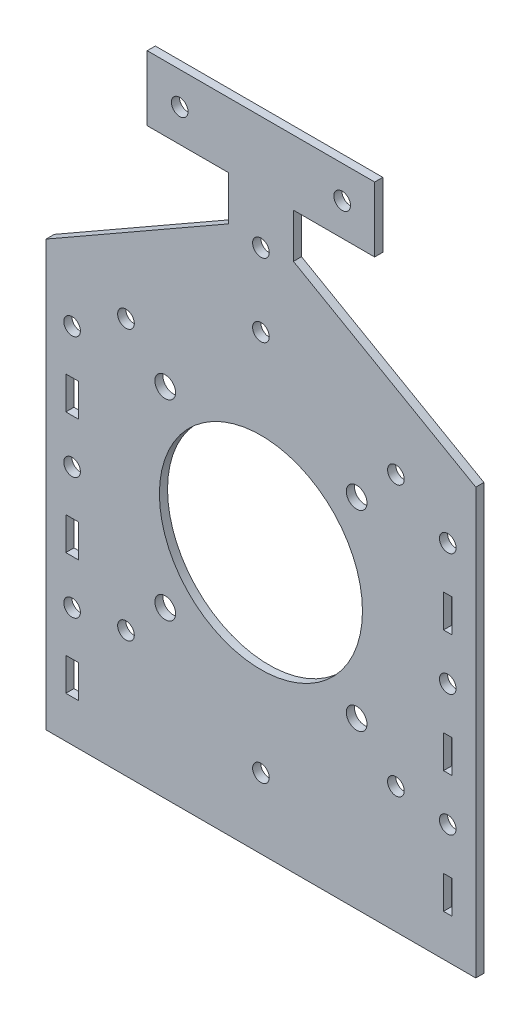
SolidWorks part; units mm, degrees
ref_plane "前视基准面" through (0, 0, 0) normal (0, 0, 1) x (1, 0, 0)
ref_plane "上视基准面" through (0, 0, 0) normal (0, 1, 0) x (1, 0, 0)
ref_plane "右视基准面" through (0, 0, 0) normal (1, 0, 0) x (0, 0, -1)
sketch "草图1" plane through (0, 0, 0) normal (0, 0, 1) x (1, 0, 0)
  line L0 (0, -36.5) -> (-46, -36.5) construction
  line L29 (-52.9, 53.8832) -> (-52.9, -50.79)
  line L32 (0, 63.5) -> (0, -36.5) construction
  line L33 (-23.57, 37.07) -> (-23.57, -10.07) construction
  line L34 (23.57, 37.07) -> (23.57, -10.07) construction
  line L38 (52.9, 53.8832) -> (52.9, -50.79)
  line L52 (-52.9, 53.8832) -> (52.9, 53.8832) construction
  line L53 (52.9, -50.79) -> (-52.9, -50.79)
  line L60 (0, 78.5) -> (0, 84.5) construction
  line L61 (-28, 106.5) -> (28, 106.5)
  line L62 (28, 106.5) -> (28, 90.5)
  line L63 (28, 90.5) -> (8, 90.5)
  line L64 (8, 90.5) -> (8, 79.5697)
  line L65 (-28, 106.5) -> (-28, 90.5)
  line L66 (-28, 90.5) -> (-8, 90.5)
  line L67 (-8, 90.5) -> (-8, 79.5697)
  line L76 (-52.9, 53.8832) -> (-8, 79.5697)
  line L77 (8, 79.5697) -> (52.9, 53.8832)
  line L78 (46, 8.5) -> (43.95, 8.5) construction
  line L79 (47.05, 19.45) -> (44.95, 27.55) construction
  line L80 (47.05, 27.55) -> (44.95, 19.45) construction
  line L81 (46, -6.5) -> (44.95, -6.5) construction
  line L82 (47.05, -10.55) -> (44.95, -2.45) construction
  line L83 (47.05, -2.45) -> (44.95, -10.55) construction
  line L84 (47.05, -40.55) -> (44.95, -32.45) construction
  line L85 (47.05, -32.45) -> (44.95, -40.55) construction
  line L86 (46, -21.5) -> (43.95, -21.5) construction
  line L87 (47.05, 19.45) -> (44.95, 19.45)
  line L88 (47.05, 19.45) -> (47.05, 27.55)
  line L89 (47.05, 27.55) -> (44.95, 27.55)
  line L90 (44.95, 19.45) -> (44.95, 27.55)
  line L91 (47.05, -10.55) -> (44.95, -10.55)
  line L92 (47.05, -10.55) -> (47.05, -2.45)
  line L93 (47.05, -2.45) -> (44.95, -2.45)
  line L94 (44.95, -10.55) -> (44.95, -2.45)
  line L95 (44.95, -32.45) -> (44.95, -40.55)
  line L96 (47.05, -40.55) -> (44.95, -40.55)
  line L97 (47.05, -32.45) -> (47.05, -40.55)
  line L98 (47.05, -32.45) -> (44.95, -32.45)
  line L101 (-44.95, 27.55) -> (-48.05, 27.55)
  line L139 (-44.95, 19.45) -> (-48.05, 19.45)
  line L140 (-44.95, 27.55) -> (-44.95, 19.45)
  line L141 (-48.05, 27.55) -> (-48.05, 19.45)
  line L142 (-44.95, -2.45) -> (-44.95, -10.55)
  line L143 (-44.95, -10.55) -> (-48.05, -10.55)
  line L144 (-44.95, -2.45) -> (-48.05, -2.45)
  line L145 (-48.05, -2.45) -> (-48.05, -10.55)
  line L146 (-44.95, -32.45) -> (-48.05, -32.45)
  line L147 (-44.95, -40.55) -> (-48.05, -40.55)
  line L148 (-44.95, -32.45) -> (-44.95, -40.55)
  line L149 (-48.05, -32.45) -> (-48.05, -40.55)
  circle A7 centre (-23.57, 37.07) radius 2.55
  circle A10 centre (-23.57, -10.07) radius 2.55
  circle A11 centre (23.57, -10.07) radius 2.55
  circle A12 centre (23.57, 37.07) radius 2.55
  circle A16 centre (0, 13.5) radius 25
  circle A17 centre (0, 13.5) radius 47 construction
  circle A18 centre (0, 60.5) radius 2.05
  circle A41 centre (33.234, 46.734) radius 2.05
  circle A43 centre (33.234, -19.734) radius 2.05
  circle A44 centre (0, -33.5) radius 2.05
  circle A45 centre (-33.234, -19.734) radius 2.05
  circle A47 centre (-33.234, 46.734) radius 2.05
  circle A48 centre (0, 78.5) radius 2.05
  circle A50 centre (-20, 98.5) radius 2.05
  circle A51 centre (20, 98.5) radius 2.05
  circle A52 centre (-47, 13.5) radius 2.05 construction
  circle A53 centre (47, 13.5) radius 2.05 construction
  circle A56 centre (46, 8.5) radius 2.05
  circle A57 centre (46, -21.5) radius 2.05
  circle A59 centre (46, 38.5) radius 2.05
  circle A63 centre (-46.5, -21.5) radius 2.05
  circle A64 centre (-46.5, 8.5) radius 2.05
  circle A65 centre (-46.5, 38.5) radius 2.05
  dimension "D3" = 5.1
  dimension "D6" = 23.57
  dimension "D10" = 65
  dimension "D16" = 4.1
  dimension "D27" = 50
  dimension "D13" = 104.6732
  dimension "D4" = 46
  dimension "D5" = 8
  dimension "D7" = 47.14
  dimension "D12" = 50
  dimension "D17" = 20
  dimension "D18" = 20
  dimension "D19" = 20
  dimension "D20" = 20
  dimension "D21" = 8
  dimension "D22" = 8
  dimension "D23" = 8
  dimension "D24" = 8
  dimension "D25" = 8
  dimension "D26" = 8
extrude "凸台-拉伸1" add sketch "草图1" along normal blind 2
